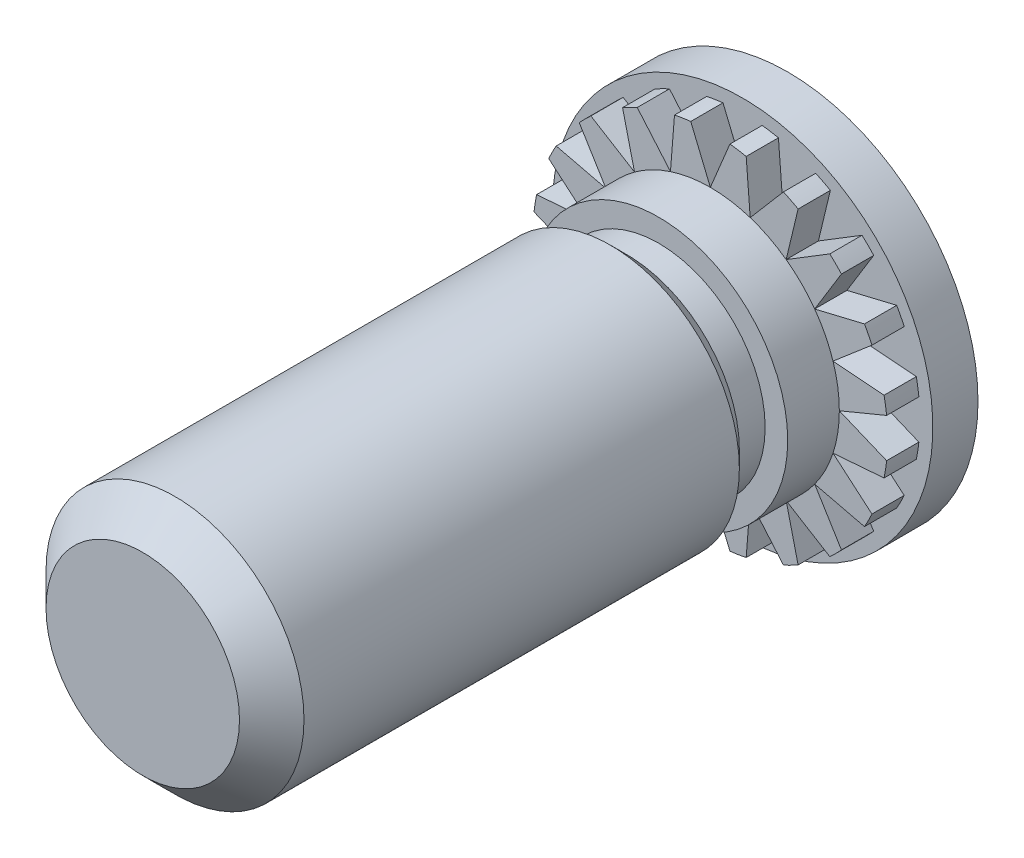
SolidWorks part; units mm, degrees
ref_plane "Спереди" through (0, 0, 0) normal (0, 0, 1) x (1, 0, 0)
ref_plane "Сверху" through (0, 0, 0) normal (0, 1, 0) x (1, 0, 0)
ref_plane "Справа" through (0, 0, 0) normal (1, 0, 0) x (0, 0, -1)
sketch "Эскиз1" plane through (0, 0, 0) normal (0, 0, 1) x (1, 0, 0)
  circle A0 centre (0, 0) radius 2.95
  dimension "D1" = 5.9
extrude "Вытянуть1" add sketch "Эскиз1" along normal blind 1.2
ref_axis "Ось1" through (0, 0, 10.6426) along (0, 0, -1)
sketch "Эскиз2" plane through (0, 0, 1.2) normal (0, 0, 1) x (1, 0, 0)
  circle A0 centre (0, 0) radius 2
  dimension "D1" = 4
extrude "Вытянуть2" add sketch "Эскиз2" along normal blind 1.9
sketch "Эскиз3" plane through (0, 0, 1.2) normal (0, 0, 1) x (1, 0, 0)
  line L0 (0, 0) -> (0, 2.95) construction
  line L1 (-0.3935, 2.95) -> (0.3935, 2.95)
  line L2 (0.3935, 2.95) -> (0, 2)
  line L3 (0, 2) -> (-0.3935, 2.95)
  circle A0 centre (0, 0) radius 2.95 construction
  circle A1 centre (0, 0) radius 2 construction
  dimension "D1" = 45
extrude "Вырез-Вытянуть1" cut sketch "Эскиз3" against normal blind 0.5
pattern_circular "Круговой массив1" count 20 over 360 about axis through (0, 0, 0) along (0, 0, 1) of "Вырез-Вытянуть1"
sketch "Эскиз4" plane through (0, 0, 0) normal (0, 1, 0) x (1, 0, 0)
  line L0 (0, -2.25) -> (2, -2.25) construction
  line L1 (0, -10.6426) -> (0, 0.6656) construction
  line L2 (-2, -3.1) -> (2, -3.1) construction
  line L3 (2, -2) -> (1.65, -2)
  line L4 (2, -2) -> (2, -2.5)
  line L5 (2, -2.5) -> (1.65, -2.5)
  line L6 (1.65, -2) -> (1.65, -2.5)
  dimension "D1" = 0.5
  dimension "D2" = 0.6
  dimension "D3" = 2
  dimension "D4" = 0.35
revolve "Вырез-Повернуть1" cut sketch "Эскиз4" angle 360 about axis through (0, 0, 10.6426) along (0, 0, -1)
sketch "Эскиз6" plane through (0, 0, 0) normal (1, 0, 0) x (0, 0, -1)
  line L0 (-3.1, 0) -> (-10, 0)
  line L1 (-3.1, 2) -> (-3.1, -2) construction
  line L2 (-10.6426, 0) -> (0.6656, 0) construction
  line L3 (-10, 0) -> (-10, -2)
  line L4 (-10, -2) -> (-3.1, -2)
  line L5 (-3.1, -2) -> (-3.1, 0)
  line L6 (0, -2.95) -> (0, 2.95) construction
  dimension "D1" = 10
  dimension "D2" = 2
revolve "Повернуть1" add sketch "Эскиз6" angle 360 about L0
chamfer "Фаска2" distance 0.5 angle 45 1 edges at (-2, 0, 10)
sketch "Эскиз7" plane through (0, 0, 1.2) normal (0, 0, 1) x (1, 0, 0)
  circle A0 centre (0, 0) radius 2.75
  circle A1 centre (0, 0) radius 2.95
  arc A2 (-1.4093, 2.5916) -> (-2.0293, 2.1412) centre (0, 0) ccw construction
  dimension "D1" = 0.2
extrude "Вырез-Вытянуть2" cut sketch "Эскиз7" against normal up to surface (0.5 mm away) up to face at (-2.4965, 0.8112, 0.7)
chamfer "Фаска3" distance 0.25 angle 45 1 edges at (2, 0, 2.5)
